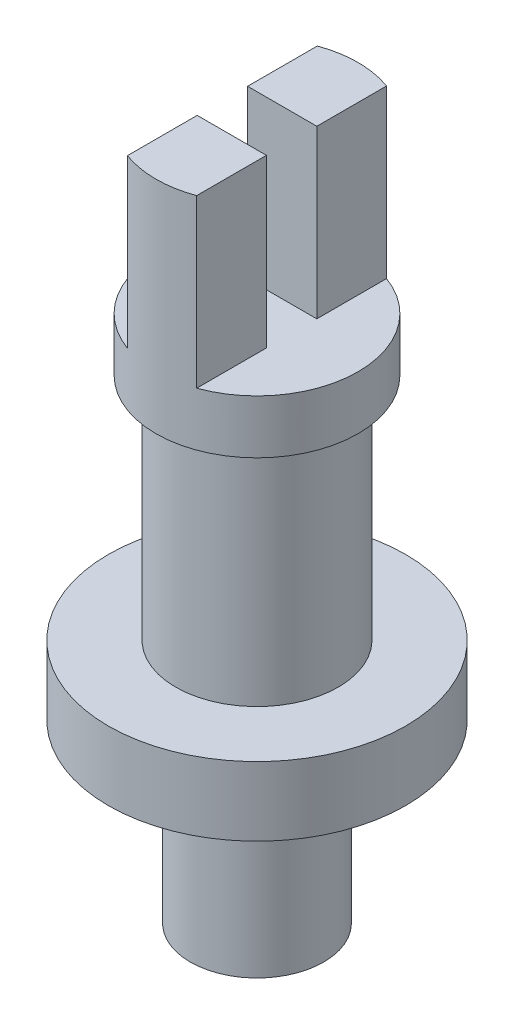
SolidWorks part; units mm, degrees
ref_plane "Alzado" through (0, 0, 0) normal (0, 0, 1) x (1, 0, 0)
ref_plane "Planta" through (0, 0, 0) normal (0, 1, 0) x (1, 0, 0)
ref_plane "Vista lateral" through (0, 0, 0) normal (1, 0, 0) x (0, 0, -1)
sketch "Croquis1" plane through (0, 0, 0) normal (1, 0, 0) x (0, 0, -1)
  line L0 (0, 0) -> (0, 12.65) construction
  line L1 (0, 0) -> (0, -4.02) construction
  line L2 (0, 0) -> (1.95, 0) construction
  line L3 (0, -4.02) -> (0, 0)
  line L4 (0, -4.02) -> (1.6, -4.02)
  line L5 (1.6, -4.02) -> (1.6, 0)
  line L6 (3.5645, 0.2104) -> (3.5645, 1.8639)
  line L7 (3.5645, 1.8639) -> (1.95, 1.8639)
  line L8 (1.95, 1.8639) -> (1.95, 7.3639)
  line L9 (1.95, 7.3639) -> (2.4232, 7.3639)
  line L10 (2.4232, 7.3639) -> (2.4232, 12.65)
  line L11 (2.4232, 12.65) -> (0, 12.65)
  line L12 (0, 12.65) -> (0, 0)
  line L13 (1.6, 0) -> (1.95, 0)
  line L14 (1.95, 0) -> (3.5645, 0.2104)
  dimension "D1" = 12.65
  dimension "D2" = 4.02
  dimension "D3" = 1.6
  dimension "D4" = 5.5
  dimension "D5" = 1.6535
revolve "Revolución1" add sketch "Croquis1" angle 360 about L12
sketch "Croquis6" plane through (0, 12.65, 0) normal (0, 1, 0) x (1, 0, 0)
  line L0 (0, 0) -> (-2.4232, 0) construction
  line L1 (-0.8299, 2.2766) -> (-0.8299, -2.2766)
  line L2 (0, 0) -> (0, 4.0624) construction
  line L3 (0, -55) -> (0, 55) construction
  line L4 (0.8299, 2.2766) -> (0.8299, -2.2766)
  circle A0 centre (0, 0) radius 2.4232 construction
  arc A1 (-0.8299, -2.2766) -> (-0.8299, 2.2766) centre (0, 0) cw
  arc A2 (0.8299, -2.2766) -> (0.8299, 2.2766) centre (0, 0) ccw
  circle M1 centre (0, 0) radius 2.4232
extrude "Cortar-Extruir1" cut sketch "Croquis6" against normal blind 4 contours L4 M1 | L1 M1
sketch "Croquis7" plane through (0, 12.65, 0) normal (0, 1, 0) x (1, 0, 0)
  line L1 (1.2999, 0.6043) -> (-1.2999, 0.6043)
  line L2 (1.2999, 0.6043) -> (1.2999, -0.6043)
  line L3 (1.2999, -0.6043) -> (-1.2999, -0.6043)
  line L4 (-1.2999, 0.6043) -> (-1.2999, -0.6043)
  line L5 (1.2999, 0.6043) -> (-1.2999, -0.6043) construction
  line L6 (1.2999, -0.6043) -> (-1.2999, 0.6043) construction
  point P0 (0, 0)
extrude "Cortar-Extruir2" cut sketch "Croquis7" against normal blind 4
